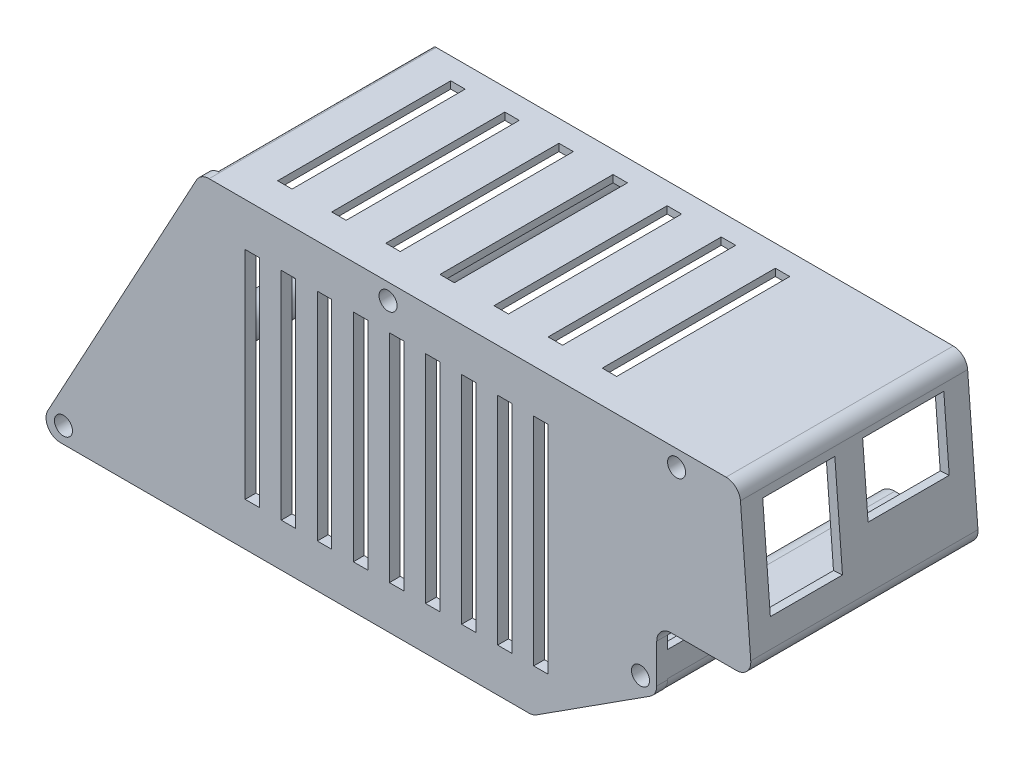
SolidWorks part; units mm, degrees
ref_plane "Front Plane" through (0, 0, 0) normal (0, 0, 1) x (1, 0, 0)
ref_plane "Top Plane" through (0, 0, 0) normal (0, 1, 0) x (1, 0, 0)
ref_plane "Right Plane" through (0, 0, 0) normal (1, 0, 0) x (0, 0, -1)
sketch "Hole layout" plane through (0, 0, 0) normal (0, 0, 1) x (1, 0, 0)
  circle A0 centre (0, 0) radius 2.5
  circle A1 centre (90, 75) radius 2.5
  circle A2 centre (170, 75) radius 2.5
  circle A3 centre (160, 20) radius 2.5
  point P9 (0, 0)
  point P10 (0, 0)
  point P11 (0, 0)
  dimension "D1" = 5
  dimension "D2" = 75
  dimension "D3" = 160
  dimension "D4" = 170
  dimension "D5" = 80
  dimension "D6" = 55
sketch "Sketch2" plane through (0, 0, 0) normal (0, 0, 1) x (1, 0, 0)
  line L0 (-2.8808, 3.457) -> (87.1192, 78.457)
  line L1 (90, 79.5) -> (170, 79.5)
  line L2 (174.4274, 74.195) -> (164.4274, 19.195)
  line L3 (160.5582, 15.5347) -> (0.5582, -4.4653)
  circle A0 centre (0, 0) radius 2.5 construction
  circle A1 centre (160, 20) radius 2.5 construction
  circle A2 centre (170, 75) radius 2.5 construction
  circle A3 centre (90, 75) radius 2.5 construction
  circle A4 centre (0, 0) radius 2.5 construction
  circle A5 centre (160, 20) radius 2.5 construction
  circle A6 centre (170, 75) radius 2.5 construction
  circle A7 centre (90, 75) radius 2.5 construction
  arc A8 (-2.8808, 3.457) -> (0.5582, -4.4653) centre (0, 0) ccw
  arc A9 (160.5582, 15.5347) -> (164.4274, 19.195) centre (160, 20) ccw
  arc A10 (174.4274, 74.195) -> (170, 79.5) centre (170, 75) ccw
  arc A11 (90, 79.5) -> (87.1192, 78.457) centre (90, 75) ccw
  circle A12 centre (0, 0) radius 4.5 construction
  circle A13 centre (160, 20) radius 4.5 construction
  circle A14 centre (170, 75) radius 4.5 construction
  circle A15 centre (90, 75) radius 4.5 construction
  circle A16 centre (90, 75) radius 2
  circle A17 centre (170, 75) radius 2
  circle A18 centre (160, 20) radius 2
  circle A19 centre (0, 0) radius 2
  point P17 (95.9791, 77.0205)
  point P29 (103.6414, 79.5)
  point P30 (102.9154, 78.4279)
  dimension "D1" = 2
  dimension "D2" = 0.5
sketch "Sketch3" plane through (0, 0, 0) normal (0, 0, 1) x (1, 0, 0)
  line L0 (181.75, 75) -> (186, 20) construction
  line L1 (183.7173, 79.5) -> (40.381, 79.5)
  line L2 (187.7054, 75.8082) -> (190.5645, 38.8082)
  line L4 (-0.84, -4.5) -> (129.0135, -4.5)
  line L5 (36.8648, 77.4071) -> (-4.3561, 1.4071)
  line L6 (186.5764, 34.5) -> (168.5, 34.5)
  line L7 (164.5, 30.5) -> (164.5, 19.7269)
  line L8 (162.6619, 16.3615) -> (131.1755, -3.8654)
  circle A0 centre (0, 0) radius 2.5 construction
  circle A1 centre (160, 20) radius 2.5 construction
  circle A2 centre (90, 75) radius 2.5 construction
  circle A3 centre (170, 75) radius 2.5 construction
  circle A4 centre (0, 0) radius 2.5
  arc A8 (162.6619, 16.3615) -> (164.5, 19.7269) centre (160.5, 19.7269) ccw
  arc A9 (-0.84, -4.5) -> (-4.3561, 1.4071) centre (-0.84, -0.5) cw
  arc A10 (40.381, 79.5) -> (36.8648, 77.4071) centre (40.381, 75.5) ccw
  arc A11 (187.7054, 75.8082) -> (183.7173, 79.5) centre (183.7173, 75.5) ccw
  arc A13 (131.1755, -3.8654) -> (129.0135, -4.5) centre (129.0135, -0.5) cw
  arc A14 (164.5, 30.5) -> (168.5, 34.5) centre (168.5, 30.5) cw
  arc A15 (186.5764, 34.5) -> (190.5645, 38.8082) centre (186.5764, 38.5) ccw
  circle A16 centre (90, 75) radius 2.5
  circle A17 centre (170, 75) radius 2.5
  circle A18 centre (160, 20) radius 2.5
  point P23 (38, 79.5)
  point P26 (187.4202, 79.5)
  point P29 (190.8974, 34.5)
  dimension "D10" = 4
  dimension "D11" = 4
  dimension "D12" = 4
  dimension "D14" = 4
  dimension "D15" = 4
  dimension "D2" = 26
  dimension "D4" = 6
  dimension "D5" = 45
  dimension "D7" = 52
  dimension "D8" = 2
  dimension "D9" = 2
extrude "Boss-Extrude5" add sketch "Sketch3" along normal blind 3
sketch "Sketch12" plane through (0, 0, 0) normal (0, 0, -1) x (-1, 0, 0)
  line L0 (-40.381, 77.5) -> (-86.2583, 77.5)
  line L1 (-185.2812, 74.7311) -> (-187.9858, 39.7311)
  line L2 (-184.9947, 36.5) -> (-167.5, 36.5)
  line L3 (-162.5, 31.5) -> (-162.5, 23.7417)
  line L4 (-158.2032, 15.8743) -> (-140.5245, 4.5175)
  line L5 (-185.2129, 75.6156) -> (-188.072, 38.6156) construction
  line L6 (-40.381, 77.5) -> (-183.7173, 77.5) construction
  line L7 (4.3561, 1.4071) -> (-36.8648, 77.4071)
  line L8 (-40.381, 79.5) -> (-183.7173, 79.5)
  line L9 (-187.7054, 75.8082) -> (-190.5645, 38.8082)
  line L10 (-186.5764, 34.5) -> (-168.5, 34.5)
  line L11 (-164.5, 30.5) -> (-164.5, 19.7269)
  line L12 (-162.6619, 16.3615) -> (-131.1755, -3.8654)
  line L13 (-129.0135, -4.5) -> (0.84, -4.5)
  line L14 (4.3561, 1.4071) -> (3.9556, 2.1455)
  line L15 (-40.381, 79.5) -> (-183.7173, 79.5)
  line L16 (-187.7054, 75.8082) -> (-190.5645, 38.8082)
  line L17 (-186.5764, 34.5) -> (-168.5, 34.5)
  line L18 (-164.5, 30.5) -> (-164.5, 19.7269)
  line L19 (-162.6619, 16.3615) -> (-141.6055, 2.8348)
  line L20 (0, -4.5) -> (0.84, -4.5)
  line L21 (-186.5764, 36.5) -> (-168.5, 36.5) construction
  line L22 (-161.581, 18.0442) -> (-130.0945, -2.1827) construction
  line L23 (-162.6619, 16.3615) -> (-131.1755, -3.8654) construction
  line L24 (-93.7417, 77.5) -> (-166.2583, 77.5)
  line L25 (-173.7417, 77.5) -> (-182.2901, 77.5)
  line L26 (-162.5, 30.5) -> (-162.5, 19.7269) construction
  arc A7 (0.84, -4.5) -> (4.3561, 1.4071) centre (0.84, -0.5) ccw
  arc A8 (-36.8648, 77.4071) -> (-40.381, 79.5) centre (-40.381, 75.5) ccw
  arc A9 (-183.7173, 79.5) -> (-187.7054, 75.8082) centre (-183.7173, 75.5) ccw
  arc A10 (-190.5645, 38.8082) -> (-186.5764, 34.5) centre (-186.5764, 38.5) ccw
  arc A11 (-164.5, 30.5) -> (-168.5, 34.5) centre (-168.5, 30.5) ccw
  arc A12 (-164.5, 19.7269) -> (-162.6619, 16.3615) centre (-160.5, 19.7269) ccw
  arc A13 (-131.1755, -3.8654) -> (-129.0135, -4.5) centre (-129.0135, -0.5) ccw
  arc A14 (0.84, -4.5) -> (4.3561, 1.4071) centre (0.84, -0.5) ccw
  arc A16 (-183.7173, 79.5) -> (-187.7054, 75.8082) centre (-183.7173, 75.5) ccw
  arc A17 (-190.5645, 38.8082) -> (-186.5764, 34.5) centre (-186.5764, 38.5) ccw
  arc A18 (-164.5, 30.5) -> (-168.5, 34.5) centre (-168.5, 30.5) ccw
  arc A19 (-164.5, 19.7269) -> (-162.6619, 16.3615) centre (-160.5, 19.7269) ccw
  circle A24 centre (-90, 75) radius 4.5
  arc A25 (-93.7417, 77.5) -> (-86.2583, 77.5) centre (-90, 75) ccw
  circle A27 centre (-170, 75) radius 4.5
  arc A28 (-173.7417, 77.5) -> (-166.2583, 77.5) centre (-170, 75) ccw
  circle A30 centre (-160, 20) radius 4.5
  arc A31 (-164.5, 20) -> (-162.4322, 16.2139) centre (-160, 20) ccw
  arc A32 (-40.381, 77.5) -> (-40.381, 79.5) centre (-40.381, 78.5) ccw
  circle A33 centre (0, 0) radius 4.5
  arc A34 (3.9556, 2.1455) -> (0, -4.5) centre (0, 0) ccw
  arc A35 (-185.2812, 74.7311) -> (-182.2901, 77.5) centre (-182.2901, 74.5) cw
  arc A36 (-184.9947, 36.5) -> (-187.9858, 39.7311) centre (-184.9947, 39.5) cw
  arc A37 (-141.6055, 2.8348) -> (-140.5245, 4.5175) centre (-141.065, 3.6762) ccw
  arc A38 (-162.5, 31.5) -> (-167.5, 36.5) centre (-167.5, 31.5) ccw
  arc A39 (-158.2032, 15.8743) -> (-162.5, 23.7417) centre (-160, 20) ccw
  circle M20 centre (-170, 75) radius 2.5
  circle M21 centre (0, 0) radius 2.5
  arc M22 (0.84, -4.5) -> (4.3561, 1.4071) centre (0.84, -0.5) ccw
  line M23 (4.3561, 1.4071) -> (-36.8648, 77.4071)
  line M25 (-40.381, 79.5) -> (-183.7173, 79.5)
  arc M26 (-183.7173, 79.5) -> (-187.7054, 75.8082) centre (-183.7173, 75.5) ccw
  line M27 (-187.7054, 75.8082) -> (-190.5645, 38.8082)
  arc M28 (-190.5645, 38.8082) -> (-186.5764, 34.5) centre (-186.5764, 38.5) ccw
  line M29 (-186.5764, 34.5) -> (-168.5, 34.5)
  arc M30 (-168.5, 34.5) -> (-164.5, 30.5) centre (-168.5, 30.5) cw
  line M31 (-164.5, 30.5) -> (-164.5, 19.7269)
  line M35 (-129.0135, -4.5) -> (0.84, -4.5)
  circle M36 centre (-90, 75) radius 2.5
  circle M37 centre (-160, 20) radius 2.5
  dimension "D10" = 3
  dimension "D11" = 3
  dimension "D13" = 5
  dimension "D12" = 25
  dimension "D1" = 0
  dimension "D2" = 2
  dimension "D3" = 2
  dimension "D4" = 2
  dimension "D5" = 2
  dimension "D6" = 2
  dimension "D7" = 2.5
  dimension "D8" = 2
  dimension "D9" = 2
extrude "Boss-Extrude6" add sketch "Sketch12" along normal blind 60 contours L4 A39 L3 A38 L2 A36 L1 A35 L25 A28 L24 A25 L0 A32 A31 L19 A37 M25 M26 M27 M28 M29 M30 M31 M36 M37 M20 | A34 M23 M35 M22 M21
sketch "Sketch13" plane through (192.4144, 14.8684, 0) normal (0.997, 0.077, 0) x (0, 0, -1)
  line L0 (54, 61.1215) -> (54, 24.0112) construction
  line L1 (-3, 61.1215) -> (60, 61.1215) construction
  line L2 (-3, 24.0112) -> (60, 24.0112) construction
  line L3 (60, 61.1215) -> (60, 24.0112) construction
  line L4 (60, 60.1215) -> (0, 60.1215) construction
  line L5 (30, 60.1215) -> (30, 39.1215) construction
  line L6 (30, 39.1215) -> (54, 39.1215) construction
  line L7 (42, 39.1215) -> (42, 60.1215) construction
  line L8 (30, 49.6215) -> (54, 49.6215) construction
  line L9 (24.5, 60.1215) -> (24.5, 24.0112) construction
  line L10 (30.75, 59.3715) -> (53.25, 59.3715)
  line L11 (30.75, 59.3715) -> (30.75, 39.8715)
  line L12 (30.75, 39.8715) -> (53.25, 39.8715)
  line L13 (53.25, 59.3715) -> (53.25, 39.8715)
  line L14 (30.75, 59.3715) -> (53.25, 39.8715) construction
  line L15 (30.75, 39.8715) -> (53.25, 59.3715) construction
  line L16 (24.5, 30.1215) -> (1.5, 30.1215) construction
  line L17 (1.5, 30.1215) -> (1.5, 60.1215) construction
  line L18 (1.5, 45.1215) -> (24.5, 45.1215) construction
  line L19 (13, 30.1215) -> (13, 60.1215) construction
  line L21 (3, 58.8715) -> (23, 58.8715)
  line L22 (3, 58.8715) -> (3, 31.3715)
  line L23 (3, 31.3715) -> (23, 31.3715)
  line L24 (23, 58.8715) -> (23, 31.3715)
  line L25 (3, 58.8715) -> (23, 31.3715) construction
  line L26 (3, 31.3715) -> (23, 58.8715) construction
  point P17 (42, 49.6215)
  point P31 (13, 45.1215)
  dimension "D1" = 6
  dimension "D2" = 1
  dimension "D3" = 24
  dimension "D4" = 21
  dimension "D5" = 22.5
  dimension "D6" = 19.5
  dimension "D7" = 5.5
  dimension "D8" = 30
  dimension "D9" = 23
  dimension "D10" = 27.5
  dimension "D11" = 20
extrude "Cut-Extrude4" cut sketch "Sketch13" against normal up to next
sketch "Earth wire" plane through (164.5, 0, 0) normal (1, 0, 0) x (0, 0, -1)
  line L0 (0, 30.5) -> (0, 19.7269) construction
  line L1 (0, 30.5) -> (9, 30.5)
  line L2 (0, 30.5) -> (0, 27)
  line L3 (0, 27) -> (9, 27)
  line L4 (9, 30.5) -> (9, 27)
  line L5 (-3, 30.5) -> (60, 30.5) construction
  dimension "D1" = 9
  dimension "D2" = 3.5
extrude "Cut-Extrude5" cut sketch "Earth wire" against normal up to next
sketch "Sketch15" plane through (0, 0, 3) normal (0, 0, 1) x (1, 0, 0)
  line L0 (183.7173, 79.5) -> (40.381, 79.5) construction
  line L1 (183.7173, 79.5) -> (40.381, 79.5) construction
  line L3 (50.381, 67.5) -> (54.381, 67.5)
  line L4 (50.381, 67.5) -> (50.381, 7.5)
  line L5 (50.381, 7.5) -> (54.381, 7.5)
  line L6 (54.381, 67.5) -> (54.381, 7.5)
  dimension "D1" = 4
  dimension "D2" = 60
  dimension "D3" = 12
  dimension "D4" = 10
extrude "Cut-Extrude6" cut sketch "Sketch15" against normal up to next
pattern_linear "LPattern1" count 9 spacing 10 along (1, 0, 0) of "Cut-Extrude6"
sketch "Sketch17" plane through (0, 79.5, 0) normal (0, 1, 0) x (1, 0, 0)
  line L0 (183.7173, 0) -> (40.381, 0) construction
  line L1 (183.7173, 0) -> (40.381, 0) construction
  line L2 (40.381, 60) -> (183.7173, 60) construction
  line L3 (50.381, 6) -> (54.381, 6)
  line L4 (50.381, 6) -> (50.381, 54)
  line L5 (50.381, 54) -> (54.381, 54)
  line L6 (54.381, 6) -> (54.381, 54)
  line L7 (40.381, 60) -> (40.381, 0) construction
  line L8 (65.381, 6) -> (65.381, 54)
  line L9 (65.381, 6) -> (69.381, 6)
  line L10 (69.381, 6) -> (69.381, 54)
  line L11 (65.381, 54) -> (69.381, 54)
  line L12 (80.381, 6) -> (80.381, 54)
  line L13 (80.381, 6) -> (84.381, 6)
  line L14 (84.381, 6) -> (84.381, 54)
  line L15 (80.381, 54) -> (84.381, 54)
  line L16 (95.381, 6) -> (95.381, 54)
  line L17 (95.381, 6) -> (99.381, 6)
  line L18 (99.381, 6) -> (99.381, 54)
  line L19 (95.381, 54) -> (99.381, 54)
  line L20 (110.381, 6) -> (110.381, 54)
  line L21 (110.381, 6) -> (114.381, 6)
  line L22 (114.381, 6) -> (114.381, 54)
  line L23 (110.381, 54) -> (114.381, 54)
  line L24 (125.381, 6) -> (125.381, 54)
  line L25 (125.381, 6) -> (129.381, 6)
  line L26 (129.381, 6) -> (129.381, 54)
  line L27 (125.381, 54) -> (129.381, 54)
  line L28 (140.381, 6) -> (140.381, 54)
  line L29 (140.381, 6) -> (144.381, 6)
  line L30 (144.381, 6) -> (144.381, 54)
  line L31 (140.381, 54) -> (144.381, 54)
  dimension "D1" = 6
  dimension "D2" = 6
  dimension "D3" = 10
  dimension "D4" = 4
  dimension "D5" = 7
extrude "Cut-Extrude8" cut sketch "Sketch17" against normal blind 60
